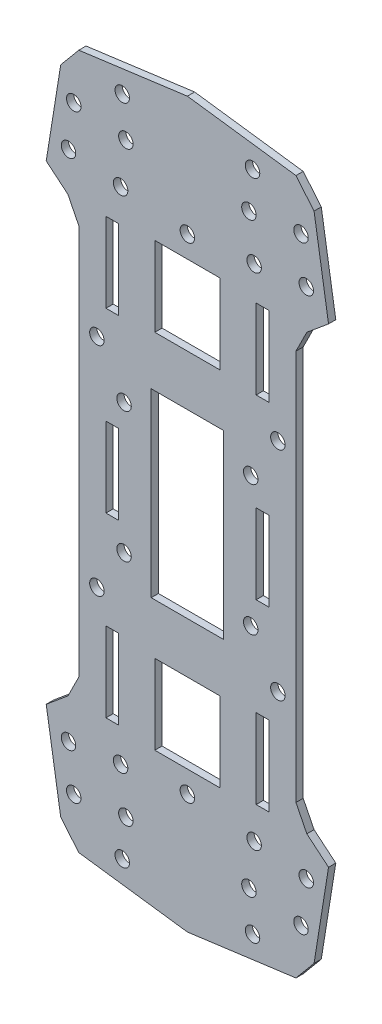
SolidWorks part; units mm, degrees
ref_plane "Front Plane" through (0, 0, 0) normal (0, 0, 1) x (1, 0, 0)
ref_plane "Top Plane" through (0, 0, 0) normal (0, 1, 0) x (1, 0, 0)
ref_plane "Right Plane" through (0, 0, 0) normal (1, 0, 0) x (0, 0, -1)
sketch "Sketch1" plane through (0, 0, 0) normal (0, 0, 1) x (1, 0, 0)
  line L0 (169.4354, 243.2996) -> (852.102, 243.2996) construction
  line L1 (-40, -100) -> (40, -100) construction
  line L2 (-40, -100) -> (-40, 100) construction
  line L3 (-40, 100) -> (40, 100) construction
  line L4 (40, -100) -> (40, 100) construction
  line L5 (-40, -100) -> (40, 100) construction
  line L6 (-40, 100) -> (40, -100) construction
  line L7 (-161.7244, -138.6454) -> (118.2756, -138.6454) construction
  line L8 (-161.7244, -138.6454) -> (-161.7244, 141.3546) construction
  line L9 (137.5032, 467.414) -> (1190.8365, 467.414) construction
  line L10 (0, -100) -> (0, 100) construction
  line L11 (0, -100) -> (-30, -96)
  line L12 (-30, -96) -> (-35, -90)
  line L13 (-35, -90) -> (-39, -65)
  line L14 (-39, -65) -> (-33, -60)
  line L15 (-33, -60) -> (-30, -54)
  line L16 (-30, -54) -> (-30, 54)
  line L17 (-17, -81) -> (-18.4483, -69.0877) construction
  line L18 (-17, -81) -> (-31.394, -82.75) construction
  line L19 (-18.4483, -69.0877) -> (-32.8423, -70.8377) construction
  line L20 (-31.394, -82.75) -> (-32.8423, -70.8377) construction
  line L21 (-22.5, -38) -> (-19, -38)
  line L22 (19, 0) -> (-19, 0) construction
  line L23 (9, -61) -> (-9, -61)
  line L24 (9, -61) -> (9, -39)
  line L25 (9, -39) -> (-9, -39)
  line L26 (-9, -61) -> (-9, -39)
  line L27 (9, -61) -> (-9, -39) construction
  line L28 (9, -39) -> (-9, -61) construction
  line L29 (-22.5, -38) -> (-22.5, -60)
  line L30 (-19, -38) -> (-19, -60)
  line L31 (-22.5, -60) -> (-19, -60)
  line L32 (-22.5, 0) -> (-40, 0) construction
  line L33 (-19, -11) -> (-22.5, -11)
  line L34 (-19, -11) -> (-19, 11)
  line L35 (-22.5, 0) -> (-19, 0) construction
  line L36 (-22.5, -11) -> (-22.5, 11)
  line L37 (22.5, 0) -> (19, 0) construction
  line L38 (22.5, 0) -> (40, 0) construction
  line L39 (31.394, -82.75) -> (32.8423, -70.8377) construction
  line L40 (18.4483, -69.0877) -> (32.8423, -70.8377) construction
  line L41 (17, -81) -> (31.394, -82.75) construction
  line L42 (17, -81) -> (18.4483, -69.0877) construction
  line L43 (22.5, -11) -> (22.5, 11)
  line L44 (19, -11) -> (19, 11)
  line L45 (19, -11) -> (22.5, -11)
  line L46 (22.5, -60) -> (19, -60)
  line L47 (19, -38) -> (19, -60)
  line L48 (22.5, -38) -> (22.5, -60)
  line L49 (9, -61) -> (9, -39)
  line L50 (22.5, -38) -> (19, -38)
  line L51 (30, -54) -> (30, 54)
  line L52 (33, -60) -> (30, -54)
  line L53 (39, -65) -> (33, -60)
  line L54 (35, -90) -> (39, -65)
  line L55 (30, -96) -> (35, -90)
  line L56 (0, -100) -> (30, -96)
  line L57 (17, 81) -> (18.4483, 69.0877) construction
  line L58 (17, 81) -> (31.394, 82.75) construction
  line L59 (18.4483, 69.0877) -> (32.8423, 70.8377) construction
  line L60 (31.394, 82.75) -> (32.8423, 70.8377) construction
  line L61 (9, 39) -> (-9, 61) construction
  line L62 (9, 61) -> (-9, 39) construction
  line L63 (-31.394, 82.75) -> (-32.8423, 70.8377) construction
  line L64 (-18.4483, 69.0877) -> (-32.8423, 70.8377) construction
  line L65 (-17, 81) -> (-31.394, 82.75) construction
  line L66 (-17, 81) -> (-18.4483, 69.0877) construction
  line L67 (-40, -100) -> (40, 100) construction
  line L68 (-40, 100) -> (40, -100) construction
  line L69 (-40, 100) -> (40, 100) construction
  line L70 (0, 100) -> (30, 96)
  line L71 (30, 96) -> (35, 90)
  line L72 (35, 90) -> (39, 65)
  line L73 (39, 65) -> (33, 60)
  line L74 (33, 60) -> (30, 54)
  line L75 (22.5, 38) -> (19, 38)
  line L76 (9, 61) -> (9, 39)
  line L77 (22.5, 38) -> (22.5, 60)
  line L78 (19, 38) -> (19, 60)
  line L79 (22.5, 60) -> (19, 60)
  line L80 (19, 11) -> (22.5, 11)
  line L81 (-19, 11) -> (-22.5, 11)
  line L82 (-22.5, 60) -> (-19, 60)
  line L83 (-19, 38) -> (-19, 60)
  line L84 (-22.5, 38) -> (-22.5, 60)
  line L85 (-9, 61) -> (-9, 39)
  line L86 (9, 39) -> (-9, 39)
  line L87 (9, 61) -> (9, 39)
  line L88 (9, 61) -> (-9, 61)
  line L89 (-22.5, 38) -> (-19, 38)
  line L90 (-33, 60) -> (-30, 54)
  line L91 (-39, 65) -> (-33, 60)
  line L92 (-35, 90) -> (-39, 65)
  line L93 (-30, 96) -> (-35, 90)
  line L94 (0, 100) -> (-30, 96)
  line L96 (-10, -25) -> (10, -25)
  line L97 (-10, -25) -> (-10, 25)
  line L98 (-10, 25) -> (10, 25)
  line L99 (10, -25) -> (10, 25)
  line L100 (-10, -25) -> (10, 25) construction
  line L101 (-10, 25) -> (10, -25) construction
  circle A0 centre (-18, -91.5) radius 2
  circle A1 centre (-17, -81) radius 2
  circle A2 centre (-31.394, -82.75) radius 2
  circle A3 centre (-32.8423, -70.8377) radius 2
  circle A4 centre (-18.4483, -69.0877) radius 2
  circle A5 centre (-25, -30) radius 2
  circle A6 centre (-17.5, -18) radius 2
  circle A7 centre (0, -67) radius 2
  circle A8 centre (17.5, -18) radius 2
  circle A9 centre (25, -30) radius 2
  circle A10 centre (18.4483, -69.0877) radius 2
  circle A11 centre (32.8423, -70.8377) radius 2
  circle A12 centre (31.394, -82.75) radius 2
  circle A13 centre (17, -81) radius 2
  circle A14 centre (18, -91.5) radius 2
  circle A15 centre (18, 91.5) radius 2
  circle A16 centre (17, 81) radius 2
  circle A17 centre (31.394, 82.75) radius 2
  circle A18 centre (32.8423, 70.8377) radius 2
  circle A19 centre (18.4483, 69.0877) radius 2
  circle A20 centre (25, 30) radius 2
  circle A21 centre (17.5, 18) radius 2
  circle A22 centre (0, 67) radius 2
  circle A23 centre (-17.5, 18) radius 2
  circle A24 centre (-25, 30) radius 2
  circle A25 centre (-18.4483, 69.0877) radius 2
  circle A26 centre (-32.8423, 70.8377) radius 2
  circle A27 centre (-31.394, 82.75) radius 2
  circle A28 centre (-17, 81) radius 2
  circle A29 centre (-18, 91.5) radius 2
  point P0 (0, 0)
  point P24 (0, -50)
  point P55 (0, 0)
  point P120 (30, 0)
  point P133 (-30, 0)
  point P137 (0, 50)
  point P138 (0, 0)
  dimension "D5" = 4
  dimension "D18" = 1
  dimension "D26" = 33
  dimension "D1" = 200
  dimension "D2" = 80
  dimension "D3" = 280
  dimension "D4" = 280
  dimension "D6" = 30
  dimension "D7" = 5
  dimension "D8" = 4
  dimension "D9" = 4
  dimension "D10" = 6
  dimension "D11" = 25
  dimension "D12" = 5
  dimension "D13" = 6
  dimension "D14" = 3
  dimension "D15" = 18
  dimension "D16" = 8.5
  dimension "D17" = 10.5
  dimension "D19" = 14.5
  dimension "D20" = 12
  dimension "D21" = 17.25
  dimension "D22" = 17.5
  dimension "D23" = 18
  dimension "D24" = 30
  dimension "D25" = 25
  dimension "D27" = 18
  dimension "D28" = 22
  dimension "D29" = 50
  dimension "D30" = 3.5
  dimension "D31" = 22
  dimension "D32" = 19
  dimension "D33" = 38
  dimension "D34" = 3.5
  dimension "D35" = 11
  dimension "D36" = 19
  dimension "D37" = 20
extrude "Boss-Extrude1" add sketch "Sketch1" along normal blind 2 contours L70 L94 L93 L92 L91 L90 L16 L15 L14 L13 L12 L11 L56 L55 L54 L53 L52 L51 L74 L73 L72 L71 A28 A26 A24 A22 A21 A20 A19 A18 A17 A16 A15 A13 A11 A9
